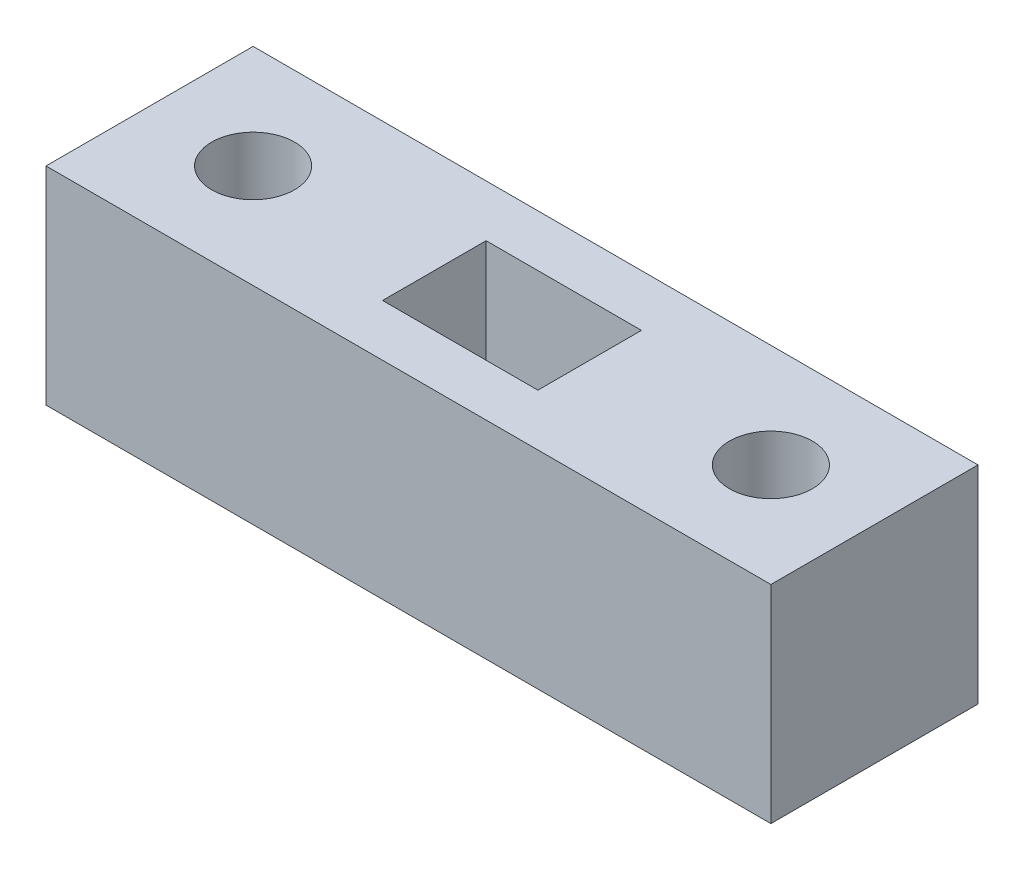
SolidWorks part; units mm, degrees
ref_plane "Front Plane" through (0, 0, 0) normal (0, 0, 1) x (1, 0, 0)
ref_plane "Top Plane" through (0, 0, 0) normal (0, 1, 0) x (1, 0, 0)
ref_plane "Right Plane" through (0, 0, 0) normal (1, 0, 0) x (0, 0, -1)
sketch "Sketch1" plane through (0, 0, 0) normal (0, 1, 0) x (1, 0, 0)
  line L0 (-35, 0) -> (35, 0) construction
  line L1 (-35, -10) -> (35, -10)
  line L2 (-35, -10) -> (-35, 10)
  line L3 (-35, 10) -> (35, 10)
  line L4 (35, -10) -> (35, 10)
  line L5 (-35, -10) -> (35, 10) construction
  line L6 (-35, 10) -> (35, -10) construction
  line L7 (0, 10) -> (0, -10) construction
  line L9 (-7.5, -5) -> (7.5, -5)
  line L10 (-7.5, -5) -> (-7.5, 5)
  line L11 (-7.5, 5) -> (7.5, 5)
  line L12 (7.5, -5) -> (7.5, 5)
  line L13 (-7.5, -5) -> (7.5, 5) construction
  line L14 (-7.5, 5) -> (7.5, -5) construction
  circle A0 centre (-25, 0) radius 4
  circle A2 centre (25, 0) radius 4
  point P0 (0, 0)
  point P14 (0, 0)
  dimension "D3" = 8
  dimension "D4" = 50
  dimension "D1" = 20
  dimension "D2" = 70
  dimension "D5" = 15
  dimension "D6" = 10
extrude "Boss-Extrude1" add sketch "Sketch1" along normal blind 20
